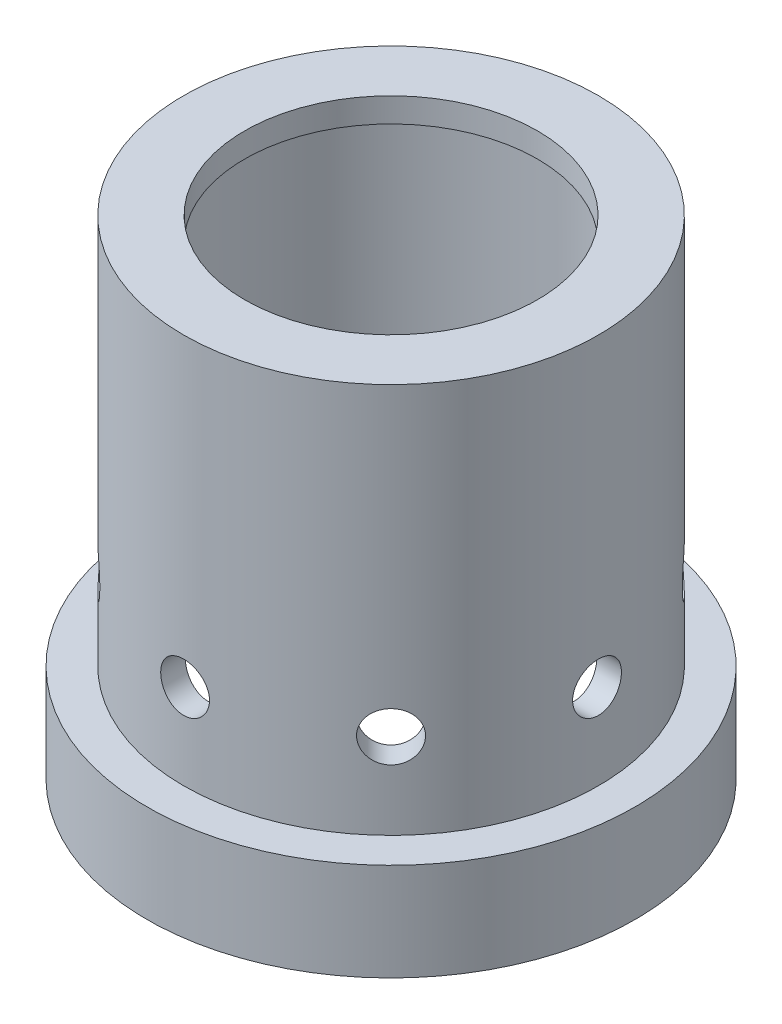
SolidWorks part; units mm, degrees
ref_plane "Front Plane" through (0, 0, 0) normal (0, 0, 1) x (1, 0, 0)
ref_plane "Top Plane" through (0, 0, 0) normal (0, 1, 0) x (1, 0, 0)
ref_plane "Right Plane" through (0, 0, 0) normal (1, 0, 0) x (0, 0, -1)
sketch "Sketch1" plane through (0, 0, 0) normal (0, 0, 1) x (1, 0, 0)
  line L0 (0, 0) -> (0, 50.8)
  line L1 (0, 50.8) -> (21.59, 50.8)
  line L2 (21.59, 50.8) -> (21.59, 10.16)
  line L3 (21.59, 10.16) -> (25.4, 10.16)
  line L4 (25.4, 10.16) -> (25.4, 0)
  line L5 (25.4, 0) -> (0, 0)
  dimension "D1" = 50.8
  dimension "D2" = 40.64
  dimension "D3" = 3.81
  dimension "D4" = 25.4
revolve "Revolve1" add sketch "Sketch1" angle 360 about L0
shell "Shell3" thickness 2.54
sketch "Sketch2" plane through (0, 50.8, 0) normal (0, 1, 0) x (1, 0, 0)
  circle A0 centre (0, 0) radius 15.24
  dimension "D1" = 30.48
extrude "Cut-Extrude2" cut sketch "Sketch2" against normal through all
sketch "Sketch3" plane through (0, 0, 0) normal (0, 0, 1) x (1, 0, 0)
  line L0 (-25.4, 0) -> (25.4, 0) construction
  circle A0 centre (0, 19.05) radius 2.54
  dimension "D1" = 5.08
  dimension "D2" = 19.05
extrude "Cut-Extrude3" cut sketch "Sketch3" against normal through all
pattern_circular "CirPattern1" count 8 every 45 about axis through (0, 50.8, 0) along (0, -1, 0) of "Cut-Extrude3"
